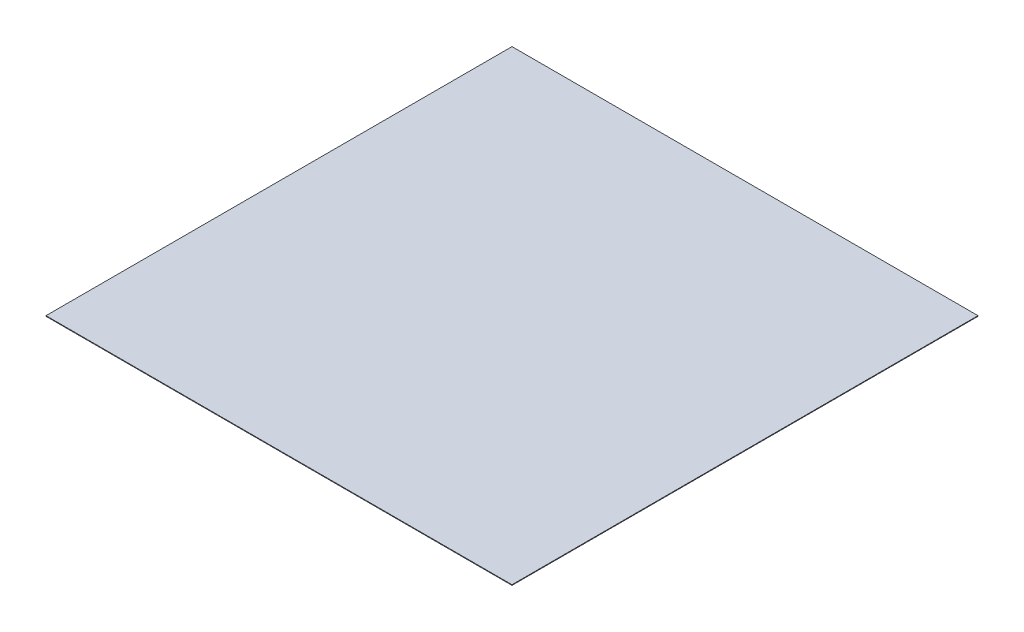
SolidWorks part; units mm, degrees
ref_plane "Front Plane" through (0, 0, 0) normal (0, 0, 1) x (1, 0, 0)
ref_plane "Top Plane" through (0, 0, 0) normal (0, 1, 0) x (1, 0, 0)
ref_plane "Right Plane" through (0, 0, 0) normal (1, 0, 0) x (0, 0, -1)
sketch "Sketch1" plane through (0, 0, 0) normal (0, 0, 1) x (1, 0, 0)
  line L0 (0, 0.5969) -> (0, -0.5969)
  line L1 (-457.2, 0) -> (457.2, 0) construction
  point P0 (-457.2, 0.5969)
  point P6 (0, 0)
  point P7 (-457.2, -0.5969)
sketch "Sketch2" plane through (0, 0, 0) normal (1, 0, 0) x (0, 0, -1)
  line L0 (457.2, 0) -> (-457.2, 0)
  line L1 (457.2, -0.5969) -> (457.2, 0.5969) construction
  point P4 (0, 0)
  point P7 (457.2, 0)
  point P8 (457.2, -0.5969)
  point P9 (457.2, 0.5969)
  dimension "D1" = 1.1938
sketch "Sketch3" plane through (0, 0, 0) normal (0, 0, 1) x (1, 0, 0)
  line L1 (457.2, 0.5969) -> (-457.2, 0.5969)
  line L2 (457.2, 0.5969) -> (457.2, -0.5969)
  line L3 (457.2, -0.5969) -> (-457.2, -0.5969)
  line L4 (-457.2, 0.5969) -> (-457.2, -0.5969)
  line L5 (457.2, 0.5969) -> (-457.2, -0.5969) construction
  line L6 (457.2, -0.5969) -> (-457.2, 0.5969) construction
  point P0 (0, 0)
extrude "Boss-Extrude1" add sketch "Sketch3" along normal up to vertex (457.2 mm away) and the other way up to vertex (457.2 mm away) up to point (0, 0, 457.2) other way up to point (0, 0, -457.2)
sketch "Sketch4" plane through (0, 0, 0) normal (0, 1, 0) x (1, 0, 0)
  line L1 (457.2, -457.2) -> (-457.2, -457.2) construction
  line L2 (457.2, -457.2) -> (457.2, 457.2) construction
  line L3 (457.2, 457.2) -> (-457.2, 457.2) construction
  line L4 (-457.2, -457.2) -> (-457.2, 457.2) construction
  line L5 (457.2, -457.2) -> (-457.2, 457.2) construction
  line L6 (457.2, 457.2) -> (-457.2, -457.2) construction
  point P0 (0, 0)
  point P6 (-457.2, 457.2)
  point P10 (457.2, 457.2)
  point P11 (457.2, -457.2)
equation "\"D1@Sketch2\"=\"Wire Dia@Sketch1\""
